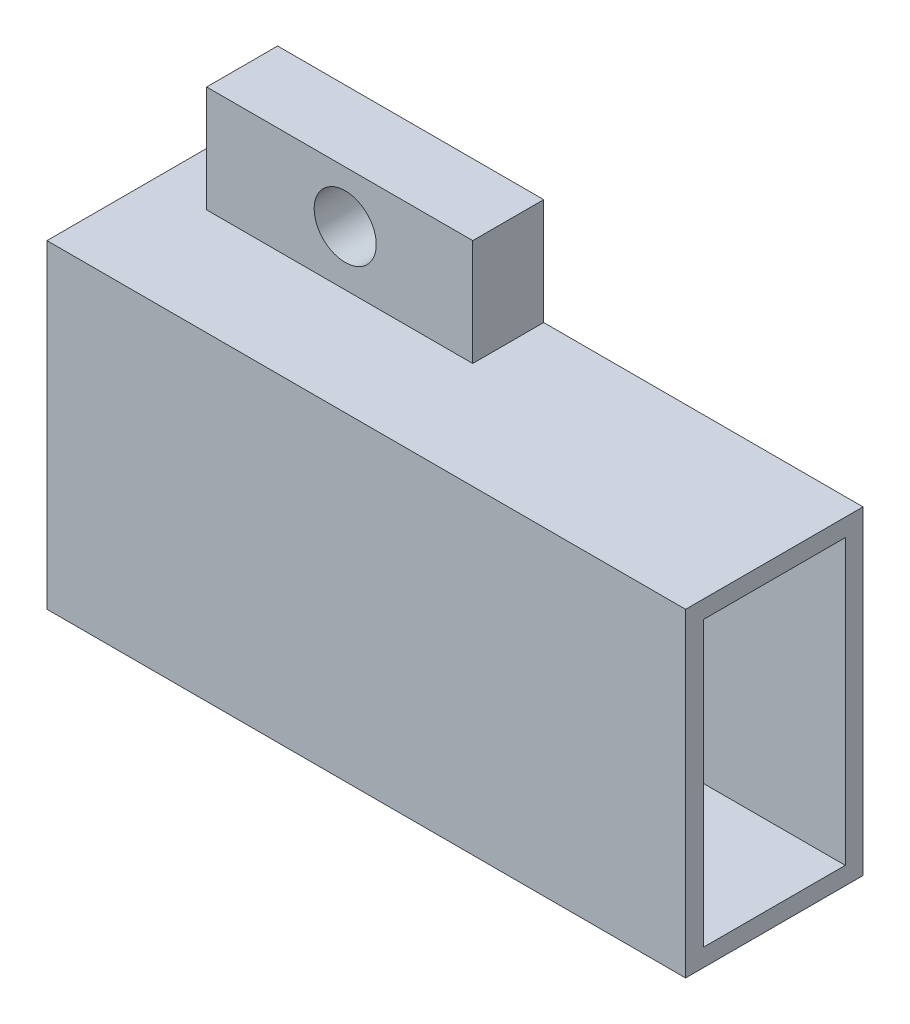
SolidWorks part; units mm, degrees
ref_plane "Front Plane" through (0, 0, 0) normal (0, 0, 1) x (1, 0, 0)
ref_plane "Top Plane" through (0, 0, 0) normal (0, 1, 0) x (1, 0, 0)
ref_plane "Right Plane" through (0, 0, 0) normal (1, 0, 0) x (0, 0, -1)
sketch "Sketch1" plane through (0, 0, 0) normal (0, 0, 1) x (1, 0, 0)
  line L1 (-18, 9) -> (18, 9)
  line L2 (-18, 9) -> (-18, -9)
  line L3 (-18, -9) -> (18, -9)
  line L4 (18, 9) -> (18, -9)
  line L5 (-18, 9) -> (18, -9) construction
  line L6 (-18, -9) -> (18, 9) construction
  point P0 (0, 0)
  dimension "D1" = 36
  dimension "D2" = 18
extrude "Boss-Extrude1" add sketch "Sketch1" along normal blind 10
shell "Shell1" thickness 1
sketch "Sketch2" plane through (-18, 0, 0) normal (-1, 0, 0) x (0, 0, 1)
  circle A0 centre (4.2218, 0) radius 3
  point P2 (4.2218, 0)
  dimension "D1" = 6
extrude "Cut-Extrude1" cut sketch "Sketch2" against normal blind 8
sketch "Sketch3" plane through (0, 0, 0) normal (0, 0, -1) x (-1, 0, 0)
  line L0 (-18, 9) -> (18, 9) construction
  line L1 (0, 9) -> (15, 9)
  line L2 (0, 9) -> (0, 15)
  line L3 (0, 15) -> (15, 15)
  line L4 (15, 9) -> (15, 15)
  line L5 (18, -9) -> (-18, -9) construction
  line L6 (0, -9) -> (15, -9)
  line L7 (0, -9) -> (0, -15)
  line L8 (0, -15) -> (15, -15)
  line L9 (15, -9) -> (15, -15)
  dimension "D1" = 15
  dimension "D2" = 6
  dimension "D3" = 15
  dimension "D4" = 6
extrude "Boss-Extrude2" add sketch "Sketch3" against normal blind 4
sketch "Sketch4" plane through (0, 0, 0) normal (0, 0, -1) x (-1, 0, 0)
  circle A0 centre (7.1891, 12.0891) radius 1.75
  circle A1 centre (7.1891, -12.0459) radius 1.75
  point P4 (7.1891, -12.0459)
  point P5 (7.1891, 12.0891)
  dimension "D1" = 3.5
  dimension "D2" = 3.5
extrude "Cut-Extrude2" cut sketch "Sketch4" against normal blind 12
